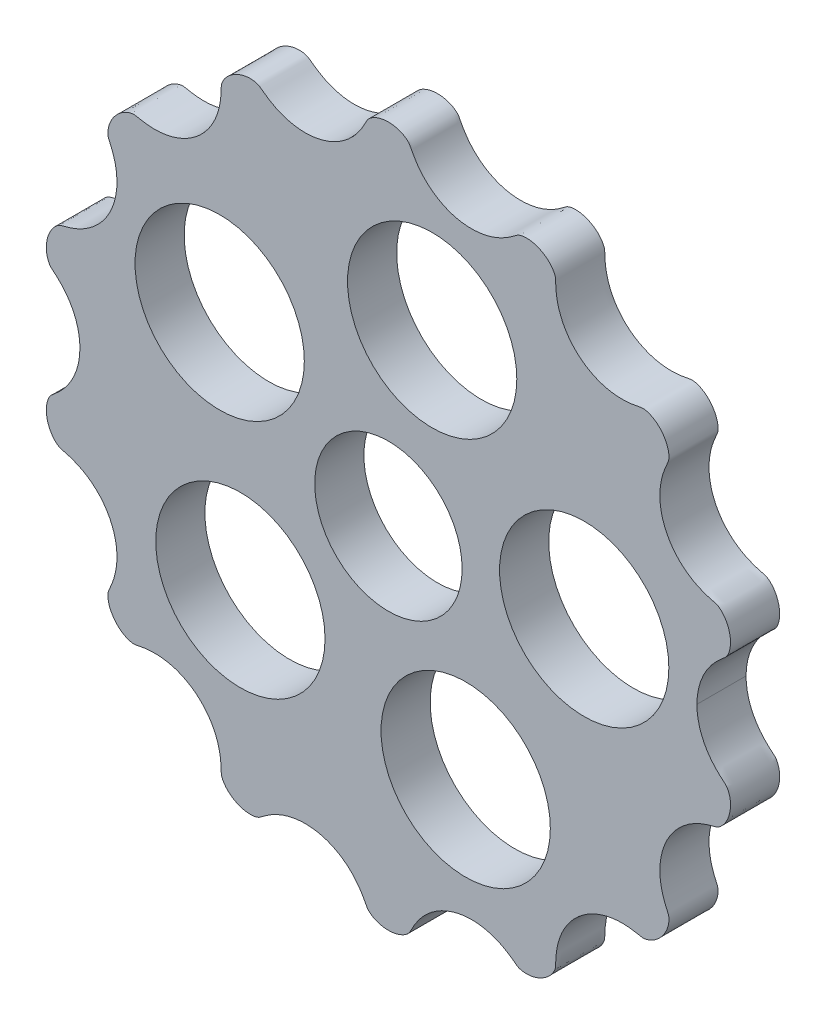
SolidWorks part; units mm, degrees
ref_plane "Front Plane" through (0, 0, 0) normal (0, 0, 1) x (1, 0, 0)
ref_plane "Top Plane" through (0, 0, 0) normal (0, 1, 0) x (1, 0, 0)
ref_plane "Right Plane" through (0, 0, 0) normal (1, 0, 0) x (0, 0, -1)
sketch "Sketch1" plane through (0, 0, 0) normal (0, 0, 1) x (1, 0, 0)
  line L0 (0, 0) -> (-50000, 0) construction
  spline S0 degree 4 poles (29.1148, 12.3034) (29.2251, 12.1678) (29.4552, 11.9043) (29.8276, 11.5337) (30.3727, 11.0937) (30.9601, 10.7121) (31.5053, 10.4321) (31.9903, 10.2313) (32.3732, 10.0998) (32.6459, 10.0172) (32.8897, 9.9508) (33.0761, 9.9023) (33.2365, 9.8624) (33.3649, 9.8232) (33.4599, 9.7833) (33.5683, 9.724) (33.7097, 9.6282) (33.879, 9.4852) (34.0743, 9.2772) (34.2676, 9.0162) (34.4376, 8.7246) (34.5807, 8.4046) (34.6855, 8.0862) (34.7563, 7.7736) (34.7922, 7.5075) (34.8058, 7.2895) (34.8069, 7.1092) (34.8014, 6.9663) (34.7862, 6.7987) (34.7706, 6.683) (34.7382, 6.5037) (34.7005, 6.3555) (34.6486, 6.1898) (34.5809, 6.02) (34.5049, 5.8706) (34.4228, 5.7426) (34.3425, 5.6471) (34.2725, 5.5788) (34.187, 5.5045) (34.0883, 5.422) (33.948, 5.3031) (33.7671, 5.1466) (33.5612, 4.9581) (33.2773, 4.6773) (32.9556, 4.3212) (32.6118, 3.8785) (32.2672, 3.3382) (31.9738, 2.7657) (31.7354, 2.1658) (31.5555, 1.5443) (31.4363, 0.9069) (31.3783, 0.2473) (31.3865, -0.4288) (31.4658, -1.1154) (31.6203, -1.8043) (31.8458, -2.4711) (32.1388, -3.1089) (32.4941, -3.7101) (32.8549, -4.1999) (33.1964, -4.5921) (33.4814, -4.8811) (33.6953, -5.0819) (33.8732, -5.2388) (34.0108, -5.3564) (34.1261, -5.4536) (34.2184, -5.5313) (34.3214, -5.6222) (34.4225, -5.7386) (34.5266, -5.9067) (34.6282, -6.1245) (34.7436, -6.4751) (34.8225, -6.9675) (34.8113, -7.5644) (34.661, -8.2417) (34.4218, -8.7837) (34.1503, -9.1912) (33.9029, -9.4619) (33.7187, -9.6221) (33.5394, -9.7456) (33.3669, -9.8285) (33.1823, -9.875) (33.0004, -9.9222) (32.782, -9.9793) (32.5292, -10.0512) (32.2433, -10.1425) (31.9268, -10.2589) (31.5377, -10.4223) (31.0835, -10.6476) (30.5742, -10.9541) (30.0282, -11.3617) (29.5242, -11.8241) (29.0684, -12.3375) (28.6707, -12.8905) (28.3339, -13.4763) (28.0598, -14.0888) (27.8495, -14.721) (27.7034, -15.3703) (27.6226, -16.0301) (27.6072, -16.6913) (27.6498, -17.2659) (27.7252, -17.7525) (27.8131, -18.1525) (27.8983, -18.4699) (27.9979, -18.7839) (28.1112, -19.094) (28.2196, -19.3578) (28.3162, -19.5777) (28.3886, -19.7384) (28.4347, -19.8413) (28.4769, -19.9459) (28.514, -20.0632) (28.5372, -20.2141) (28.546, -20.4211) (28.5287, -20.6643) (28.4793, -20.9385) (28.3904, -21.239) (28.2361, -21.6133) (27.9894, -22.0397) (27.6291, -22.4842) (27.199, -22.8485) (26.7944, -23.0902) (26.4653, -23.2258) (26.2334, -23.2927) (26.0388, -23.3257) (25.8855, -23.3344) (25.7494, -23.3208) (25.6312, -23.2987) (25.5035, -23.273) (25.3658, -23.2457) (25.1784, -23.2099) (24.8616, -23.1554) (24.425, -23.0993) (23.8669, -23.0674) (23.2277, -23.0884) (22.5933, -23.1683) (21.9654, -23.3085) (21.3502, -23.5092) (20.7566, -23.7687) (20.1904, -24.0849) (19.6475, -24.4614) (19.1353, -24.898) (18.6611, -25.3942) (18.2334, -25.9477) (17.8666, -26.541) (17.564, -27.1671) (17.3278, -27.818) (17.1796, -28.4029) (17.0935, -28.9116) (17.0509, -29.3082) (17.0309, -29.5904) (17.0202, -29.8431) (17.0147, -30.024) (17.0118, -30.1633) (17.0063, -30.2747) (16.9973, -30.3772) (16.9693, -30.5107) (16.9011, -30.6949) (16.7913, -30.9103) (16.5868, -31.2168) (16.2505, -31.5811) (15.7762, -31.9413) (15.1518, -32.2436) (14.5767, -32.3922) (14.0855, -32.431) (13.7189, -32.4031) (13.4803, -32.3569) (13.2942, -32.2977) (13.1612, -32.2347) (13.057, -32.1661) (12.9743, -32.1051) (12.872, -32.0278) (12.749, -31.9353) (12.5773, -31.8086) (12.354, -31.6518) (12.0257, -31.4379) (11.5814, -31.1844) (11.0404, -30.9303) (10.3942, -30.7013) (9.7255, -30.5379) (8.8696, -30.4195) (7.848, -30.4197) (6.8473, -30.5909) (5.9007, -30.9223) (5.1715, -31.2902) (4.6199, -31.6398) (4.1067, -32.0394) (3.6361, -32.4843) (3.2632, -32.9099) (2.973, -33.297) (2.7505, -33.6331) (2.6046, -33.8748) (2.4861, -34.0858) (2.3942, -34.2578) (2.3258, -34.3891) (2.2611, -34.5147) (2.1993, -34.6346) (2.1237, -34.762) (2.0189, -34.8849) (1.8703, -35.0205) (1.6749, -35.1617) (1.435, -35.2974) (1.1501, -35.4193) (0.7695, -35.5374) (0.2868, -35.6195) (-0.2046, -35.6253) (-0.6907, -35.5547) (-1.0776, -35.4449) (-1.3681, -35.3293) (-1.6139, -35.199) (-1.8161, -35.0628) (-1.9708, -34.931) (-2.084, -34.8131) (-2.1593, -34.7039) (-2.2091, -34.6147) (-2.2564, -34.5243) (-2.306, -34.4275) (-2.3668, -34.31) (-2.4588, -34.136) (-2.577, -33.9223) (-2.7226, -33.6774) (-2.945, -33.3365) (-3.2355, -32.9437) (-3.6093, -32.5119) (-4.0817, -32.0607) (-4.5974, -31.6554) (-5.1525, -31.3008) (-5.8873, -30.9274) (-6.8394, -30.5923) (-7.8448, -30.4197) (-8.8696, -30.4195) (-9.7255, -30.5379) (-10.3942, -30.7013) (-11.0404, -30.9303) (-11.5814, -31.1844) (-12.0257, -31.4379) (-12.354, -31.6518) (-12.5773, -31.8086) (-12.749, -31.9353) (-12.872, -32.0278) (-12.9743, -32.1051) (-13.057, -32.1661) (-13.1612, -32.2347) (-13.2942, -32.2977) (-13.4803, -32.3569) (-13.7189, -32.4031) (-14.0855, -32.431) (-14.5767, -32.3922) (-15.1518, -32.2436) (-15.7762, -31.9413) (-16.2505, -31.5811) (-16.5868, -31.2168) (-16.7913, -30.9103) (-16.9011, -30.6949) (-16.9693, -30.5107) (-16.9973, -30.3772) (-17.0063, -30.2747) (-17.0118, -30.1633) (-17.0147, -30.024) (-17.0202, -29.8431) (-17.0309, -29.5904) (-17.0509, -29.3082) (-17.0935, -28.9116) (-17.1796, -28.4029) (-17.3278, -27.818) (-17.564, -27.1671) (-17.8666, -26.541) (-18.2334, -25.9477) (-18.6611, -25.3942) (-19.1353, -24.898) (-19.6475, -24.4614) (-20.1904, -24.0849) (-20.7566, -23.7687) (-21.3502, -23.5092) (-21.9654, -23.3085) (-22.5933, -23.1683) (-23.2277, -23.0884) (-23.8669, -23.0674) (-24.425, -23.0993) (-24.8616, -23.1554) (-25.1784, -23.2099) (-25.3658, -23.2457) (-25.5035, -23.273) (-25.6312, -23.2987) (-25.7494, -23.3208) (-25.8855, -23.3344) (-26.0388, -23.3257) (-26.2334, -23.2927) (-26.4653, -23.2258) (-26.7944, -23.0902) (-27.199, -22.8485) (-27.6291, -22.4842) (-27.9894, -22.0397) (-28.2361, -21.6133) (-28.3904, -21.239) (-28.4793, -20.9385) (-28.5287, -20.6643) (-28.546, -20.4211) (-28.5372, -20.2141) (-28.514, -20.0632) (-28.4769, -19.9459) (-28.4347, -19.8413) (-28.3886, -19.7384) (-28.3162, -19.5777) (-28.2196, -19.3578) (-28.1112, -19.094) (-27.9979, -18.7839) (-27.8983, -18.4699) (-27.8131, -18.1525) (-27.7252, -17.7525) (-27.6498, -17.2659) (-27.6072, -16.6913) (-27.6226, -16.0301) (-27.7034, -15.3703) (-27.8495, -14.721) (-28.0598, -14.0888) (-28.3339, -13.4763) (-28.6707, -12.8905) (-29.0684, -12.3375) (-29.5242, -11.8241) (-30.0282, -11.3617) (-30.5742, -10.9541) (-31.0835, -10.6476) (-31.5377, -10.4223) (-31.9268, -10.2589) (-32.2433, -10.1425) (-32.5292, -10.0512) (-32.782, -9.9793) (-33.0004, -9.9222) (-33.1823, -9.875) (-33.3669, -9.8285) (-33.5394, -9.7456) (-33.7187, -9.6221) (-33.9029, -9.4619) (-34.1503, -9.1912) (-34.4218, -8.7837) (-34.661, -8.2417) (-34.8113, -7.5644) (-34.8225, -6.9675) (-34.7436, -6.4751) (-34.6282, -6.1245) (-34.5266, -5.9067) (-34.4225, -5.7386) (-34.3214, -5.6222) (-34.2184, -5.5313) (-34.1261, -5.4536) (-34.0108, -5.3564) (-33.8732, -5.2388) (-33.6953, -5.0819) (-33.4814, -4.8811) (-33.1964, -4.5921) (-32.8549, -4.1999) (-32.4941, -3.7101) (-32.1388, -3.1089) (-31.8458, -2.4711) (-31.6203, -1.8043) (-31.4658, -1.1154) (-31.3865, -0.4288) (-31.3783, 0.2473) (-31.4363, 0.9069) (-31.5555, 1.5443) (-31.7354, 2.1658) (-31.9738, 2.7657) (-32.2672, 3.3382) (-32.6118, 3.8785) (-32.9556, 4.3212) (-33.2773, 4.6773) (-33.5612, 4.9581) (-33.7671, 5.1466) (-33.948, 5.3031) (-34.0883, 5.422) (-34.187, 5.5045) (-34.2725, 5.5788) (-34.3425, 5.6471) (-34.4228, 5.7426) (-34.5049, 5.8706) (-34.5809, 6.02) (-34.6486, 6.1898) (-34.7005, 6.3555) (-34.7382, 6.5037) (-34.7706, 6.683) (-34.7862, 6.7987) (-34.8014, 6.9663) (-34.8069, 7.1092) (-34.8058, 7.2895) (-34.7922, 7.5075) (-34.7563, 7.7736) (-34.6855, 8.0862) (-34.5807, 8.4046) (-34.4376, 8.7246) (-34.2676, 9.0162) (-34.0743, 9.2772) (-33.879, 9.4852) (-33.7097, 9.6282) (-33.5683, 9.724) (-33.4599, 9.7833) (-33.3649, 9.8232) (-33.2365, 9.8624) (-33.0761, 9.9023) (-32.8897, 9.9508) (-32.6459, 10.0172) (-32.3732, 10.0998) (-31.9903, 10.2313) (-31.5053, 10.4321) (-30.9601, 10.7121) (-30.3727, 11.0937) (-29.8276, 11.5337) (-29.4552, 11.9043) (-29.2251, 12.1678) (-29.1148, 12.3034) knots 0 0 0 0 0 0.004405 0.008809 0.013214 0.01762 0.022025 0.024227 0.02643 0.027817 0.029205 0.030592 0.031286 0.031979 0.032583 0.033187 0.034394 0.036274 0.038154 0.040358 0.042562 0.044765 0.046967 0.048794 0.050621 0.051534 0.052447 0.053361 0.054274 0.055285 0.056296 0.057308 0.058319 0.059613 0.060907 0.061522 0.062138 0.062754 0.06337 0.064374 0.065379 0.067388 0.069397 0.071406 0.075439 0.079471 0.083501 0.087531 0.091623 0.095714 0.099779 0.103843 0.108282 0.112722 0.117161 0.121601 0.125988 0.130375 0.134727 0.136903 0.13908 0.1406 0.14212 0.14288 0.14364 0.1444 0.14516 0.146336 0.147512 0.14936 0.151209 0.15561 0.160014 0.164295 0.16858 0.170438 0.172297 0.173509 0.174721 0.175908 0.177095 0.178282 0.179469 0.181593 0.183717 0.185841 0.187965 0.192223 0.19648 0.200793 0.205106 0.209428 0.213749 0.217927 0.222104 0.226307 0.23051 0.234668 0.238827 0.242946 0.245005 0.247065 0.249144 0.251223 0.253303 0.255382 0.256328 0.257274 0.257748 0.258221 0.259167 0.260371 0.261575 0.263436 0.265296 0.267377 0.269458 0.273617 0.277665 0.281712 0.283577 0.285441 0.286612 0.287783 0.288539 0.289296 0.290053 0.290809 0.291822 0.292834 0.294859 0.29891 0.302906 0.306903 0.310951 0.314999 0.319092 0.323184 0.327249 0.331314 0.335714 0.340113 0.344511 0.348908 0.353257 0.357607 0.361927 0.364088 0.366248 0.367652 0.369056 0.37046 0.370811 0.371162 0.371864 0.373051 0.374238 0.376092 0.377946 0.382309 0.386671 0.390993 0.395318 0.397173 0.399028 0.40023 0.401432 0.402078 0.402725 0.403371 0.404018 0.40531 0.406603 0.408748 0.410892 0.415181 0.419482 0.423784 0.42814 0.432496 0.441216 0.449419 0.453546 0.457674 0.461762 0.465851 0.469909 0.473968 0.476 0.478032 0.480064 0.48108 0.482096 0.482945 0.483794 0.484643 0.485492 0.486669 0.487847 0.489701 0.491555 0.493598 0.495641 0.499725 0.503848 0.50591 0.507972 0.509842 0.511712 0.512906 0.514101 0.514957 0.515814 0.516243 0.516671 0.517528 0.518553 0.519579 0.521629 0.52368 0.525731 0.529831 0.533932 0.538049 0.542166 0.546333 0.550501 0.558784 0.567504 0.57186 0.576216 0.580518 0.584819 0.589108 0.591252 0.593397 0.59469 0.595982 0.596629 0.597275 0.597922 0.598568 0.59977 0.600972 0.602827 0.604682 0.609007 0.613329 0.617691 0.622054 0.623908 0.625762 0.626949 0.628136 0.628838 0.629189 0.62954 0.630944 0.632348 0.633752 0.635912 0.638073 0.642393 0.646743 0.651092 0.655489 0.659887 0.664286 0.668686 0.672751 0.676816 0.680908 0.685001 0.689049 0.693097 0.697094 0.70109 0.705141 0.707166 0.708178 0.709191 0.709947 0.710704 0.711461 0.712217 0.713388 0.714559 0.716423 0.718288 0.722335 0.726383 0.730542 0.732623 0.734704 0.736564 0.738425 0.739629 0.740833 0.741779 0.742252 0.742726 0.743672 0.744618 0.746697 0.748777 0.750856 0.752935 0.754995 0.757054 0.761173 0.765332 0.76949 0.773693 0.777896 0.782073 0.786251 0.790572 0.794894 0.799207 0.80352 0.807777 0.812035 0.814159 0.816283 0.818407 0.820531 0.821718 0.822905 0.824092 0.825279 0.826491 0.827703 0.829562 0.83142 0.835705 0.839986 0.84439 0.848791 0.85064 0.852488 0.853664 0.85484 0.8556 0.85636 0.85712 0.85788 0.8594 0.86092 0.863097 0.865273 0.869625 0.874012 0.878399 0.882839 0.887278 0.891718 0.896157 0.900221 0.904286 0.908377 0.912469 0.916499 0.920529 0.924561 0.928594 0.930603 0.932612 0.934621 0.935626 0.93663 0.937246 0.937862 0.938478 0.939093 0.940387 0.941681 0.942692 0.943704 0.944715 0.945726 0.946639 0.947553 0.948466 0.949379 0.951206 0.953033 0.955235 0.957438 0.959642 0.961846 0.963726 0.965606 0.966813 0.967417 0.968021 0.968714 0.969408 0.970795 0.972183 0.97357 0.975773 0.977975 0.98238 0.986786 0.991191 0.995595 1 1 1 1 1 construction
  spline S1 degree 4 poles (31.3875, 0) (31.3875, -0.1914) (31.4016, -0.559) (31.4625, -1.1005) (31.6203, -1.8043) (31.8458, -2.4711) (32.1388, -3.1089) (32.4941, -3.7101) (32.8549, -4.1999) (33.1964, -4.5921) (33.4814, -4.8811) (33.6953, -5.0819) (33.8732, -5.2388) (34.0108, -5.3564) (34.1261, -5.4536) (34.2184, -5.5313) (34.3214, -5.6222) (34.4225, -5.7386) (34.5266, -5.9067) (34.6282, -6.1245) (34.7436, -6.4751) (34.8225, -6.9675) (34.8113, -7.5644) (34.661, -8.2417) (34.4218, -8.7837) (34.1503, -9.1912) (33.9029, -9.4619) (33.7187, -9.6221) (33.5394, -9.7456) (33.3669, -9.8285) (33.1823, -9.875) (33.0004, -9.9222) (32.782, -9.9793) (32.5292, -10.0512) (32.2433, -10.1425) (31.9268, -10.2589) (31.5377, -10.4223) (31.0835, -10.6476) (30.5742, -10.9541) (30.0282, -11.3617) (29.5242, -11.8241) (29.0684, -12.3375) (28.6707, -12.8905) (28.3339, -13.4763) (28.0598, -14.0888) (27.8495, -14.721) (27.7034, -15.3703) (27.6226, -16.0301) (27.6072, -16.6913) (27.6498, -17.2659) (27.7252, -17.7525) (27.8131, -18.1525) (27.8983, -18.4699) (27.9979, -18.7839) (28.1112, -19.094) (28.2196, -19.3578) (28.3162, -19.5777) (28.3886, -19.7384) (28.4347, -19.8413) (28.4769, -19.9459) (28.514, -20.0632) (28.5372, -20.2141) (28.546, -20.4211) (28.5287, -20.6643) (28.4793, -20.9385) (28.3904, -21.239) (28.2361, -21.6133) (27.9894, -22.0397) (27.6291, -22.4842) (27.199, -22.8485) (26.7944, -23.0902) (26.4653, -23.2258) (26.2334, -23.2927) (26.0388, -23.3257) (25.8855, -23.3344) (25.7494, -23.3208) (25.6312, -23.2987) (25.5035, -23.273) (25.3658, -23.2457) (25.1784, -23.2099) (24.8616, -23.1554) (24.425, -23.0993) (23.8669, -23.0674) (23.2277, -23.0884) (22.5933, -23.1683) (21.9654, -23.3085) (21.3502, -23.5092) (20.7566, -23.7687) (20.1904, -24.0849) (19.6475, -24.4614) (19.1353, -24.898) (18.6611, -25.3942) (18.2334, -25.9477) (17.8666, -26.541) (17.564, -27.1671) (17.3278, -27.818) (17.1796, -28.4029) (17.0935, -28.9116) (17.0509, -29.3082) (17.0309, -29.5904) (17.0202, -29.8431) (17.0147, -30.024) (17.0118, -30.1633) (17.0063, -30.2747) (16.9973, -30.3772) (16.9693, -30.5107) (16.9011, -30.6949) (16.7913, -30.9103) (16.5868, -31.2168) (16.2505, -31.5811) (15.7762, -31.9413) (15.1518, -32.2436) (14.5767, -32.3922) (14.0855, -32.431) (13.7189, -32.4031) (13.4803, -32.3569) (13.2942, -32.2977) (13.1612, -32.2347) (13.057, -32.1661) (12.9743, -32.1051) (12.872, -32.0278) (12.749, -31.9353) (12.5773, -31.8086) (12.354, -31.6518) (12.0257, -31.4379) (11.5814, -31.1844) (11.0404, -30.9303) (10.3942, -30.7013) (9.7255, -30.5379) (8.8696, -30.4195) (7.848, -30.4197) (6.8473, -30.5909) (5.9007, -30.9223) (5.1715, -31.2902) (4.6199, -31.6398) (4.1067, -32.0394) (3.6361, -32.4843) (3.2632, -32.9099) (2.973, -33.297) (2.7505, -33.6331) (2.6046, -33.8748) (2.4861, -34.0858) (2.3942, -34.2578) (2.3258, -34.3891) (2.2611, -34.5147) (2.1993, -34.6346) (2.1237, -34.762) (2.0189, -34.8849) (1.8703, -35.0205) (1.6749, -35.1617) (1.435, -35.2974) (1.1501, -35.4193) (0.7695, -35.5374) (0.2868, -35.6195) (-0.2046, -35.6253) (-0.6907, -35.5547) (-1.0776, -35.4449) (-1.3681, -35.3293) (-1.6139, -35.199) (-1.8161, -35.0628) (-1.9708, -34.931) (-2.084, -34.8131) (-2.1593, -34.7039) (-2.2091, -34.6147) (-2.2564, -34.5243) (-2.306, -34.4275) (-2.3668, -34.31) (-2.4588, -34.136) (-2.577, -33.9223) (-2.7226, -33.6774) (-2.945, -33.3365) (-3.2355, -32.9437) (-3.6093, -32.5119) (-4.0817, -32.0607) (-4.5974, -31.6554) (-5.1525, -31.3008) (-5.8873, -30.9274) (-6.8394, -30.5923) (-7.8448, -30.4197) (-8.8696, -30.4195) (-9.7255, -30.5379) (-10.3942, -30.7013) (-11.0404, -30.9303) (-11.5814, -31.1844) (-12.0257, -31.4379) (-12.354, -31.6518) (-12.5773, -31.8086) (-12.749, -31.9353) (-12.872, -32.0278) (-12.9743, -32.1051) (-13.057, -32.1661) (-13.1612, -32.2347) (-13.2942, -32.2977) (-13.4803, -32.3569) (-13.7189, -32.4031) (-14.0855, -32.431) (-14.5767, -32.3922) (-15.1518, -32.2436) (-15.7762, -31.9413) (-16.2505, -31.5811) (-16.5868, -31.2168) (-16.7913, -30.9103) (-16.9011, -30.6949) (-16.9693, -30.5107) (-16.9973, -30.3772) (-17.0063, -30.2747) (-17.0118, -30.1633) (-17.0147, -30.024) (-17.0202, -29.8431) (-17.0309, -29.5904) (-17.0509, -29.3082) (-17.0935, -28.9116) (-17.1796, -28.4029) (-17.3278, -27.818) (-17.564, -27.1671) (-17.8666, -26.541) (-18.2334, -25.9477) (-18.6611, -25.3942) (-19.1353, -24.898) (-19.6475, -24.4614) (-20.1904, -24.0849) (-20.7566, -23.7687) (-21.3502, -23.5092) (-21.9654, -23.3085) (-22.5933, -23.1683) (-23.2277, -23.0884) (-23.8669, -23.0674) (-24.425, -23.0993) (-24.8616, -23.1554) (-25.1784, -23.2099) (-25.3658, -23.2457) (-25.5035, -23.273) (-25.6312, -23.2987) (-25.7494, -23.3208) (-25.8855, -23.3344) (-26.0388, -23.3257) (-26.2334, -23.2927) (-26.4653, -23.2258) (-26.7944, -23.0902) (-27.199, -22.8485) (-27.6291, -22.4842) (-27.9894, -22.0397) (-28.2361, -21.6133) (-28.3904, -21.239) (-28.4793, -20.9385) (-28.5287, -20.6643) (-28.546, -20.4211) (-28.5372, -20.2141) (-28.514, -20.0632) (-28.4769, -19.9459) (-28.4347, -19.8413) (-28.3886, -19.7384) (-28.3162, -19.5777) (-28.2196, -19.3578) (-28.1112, -19.094) (-27.9979, -18.7839) (-27.8983, -18.4699) (-27.8131, -18.1525) (-27.7252, -17.7525) (-27.6498, -17.2659) (-27.6072, -16.6913) (-27.6226, -16.0301) (-27.7034, -15.3703) (-27.8495, -14.721) (-28.0598, -14.0888) (-28.3339, -13.4763) (-28.6707, -12.8905) (-29.0684, -12.3375) (-29.5242, -11.8241) (-30.0282, -11.3617) (-30.5742, -10.9541) (-31.0835, -10.6476) (-31.5377, -10.4223) (-31.9268, -10.2589) (-32.2433, -10.1425) (-32.5292, -10.0512) (-32.782, -9.9793) (-33.0004, -9.9222) (-33.1823, -9.875) (-33.3669, -9.8285) (-33.5394, -9.7456) (-33.7187, -9.6221) (-33.9029, -9.4619) (-34.1503, -9.1912) (-34.4218, -8.7837) (-34.661, -8.2417) (-34.8113, -7.5644) (-34.8225, -6.9675) (-34.7436, -6.4751) (-34.6282, -6.1245) (-34.5266, -5.9067) (-34.4225, -5.7386) (-34.3214, -5.6222) (-34.2184, -5.5313) (-34.1261, -5.4536) (-34.0108, -5.3564) (-33.8732, -5.2388) (-33.6953, -5.0819) (-33.4814, -4.8811) (-33.1964, -4.5921) (-32.8549, -4.1999) (-32.4941, -3.7101) (-32.1388, -3.1089) (-31.8458, -2.4711) (-31.5589, -1.6226) (-31.4275, -0.9114) (-31.3875, -0.3676) (-31.3875, 0) knots 0.103459 0.103459 0.103459 0.103459 0.103459 0.108282 0.112722 0.117161 0.121601 0.125988 0.130375 0.134727 0.136903 0.13908 0.1406 0.14212 0.14288 0.14364 0.1444 0.14516 0.146336 0.147512 0.14936 0.151209 0.15561 0.160014 0.164295 0.16858 0.170438 0.172297 0.173509 0.174721 0.175908 0.177095 0.178282 0.179469 0.181593 0.183717 0.185841 0.187965 0.192223 0.19648 0.200793 0.205106 0.209428 0.213749 0.217927 0.222104 0.226307 0.23051 0.234668 0.238827 0.242946 0.245005 0.247065 0.249144 0.251223 0.253303 0.255382 0.256328 0.257274 0.257748 0.258221 0.259167 0.260371 0.261575 0.263436 0.265296 0.267377 0.269458 0.273617 0.277665 0.281712 0.283577 0.285441 0.286612 0.287783 0.288539 0.289296 0.290053 0.290809 0.291822 0.292834 0.294859 0.29891 0.302906 0.306903 0.310951 0.314999 0.319092 0.323184 0.327249 0.331314 0.335714 0.340113 0.344511 0.348908 0.353257 0.357607 0.361927 0.364088 0.366248 0.367652 0.369056 0.37046 0.370811 0.371162 0.371864 0.373051 0.374238 0.376092 0.377946 0.382309 0.386671 0.390993 0.395318 0.397173 0.399028 0.40023 0.401432 0.402078 0.402725 0.403371 0.404018 0.40531 0.406603 0.408748 0.410892 0.415181 0.419482 0.423784 0.42814 0.432496 0.441216 0.449419 0.453546 0.457674 0.461762 0.465851 0.469909 0.473968 0.476 0.478032 0.480064 0.48108 0.482096 0.482945 0.483794 0.484643 0.485492 0.486669 0.487847 0.489701 0.491555 0.493598 0.495641 0.499725 0.503848 0.50591 0.507972 0.509842 0.511712 0.512906 0.514101 0.514957 0.515814 0.516243 0.516671 0.517528 0.518553 0.519579 0.521629 0.52368 0.525731 0.529831 0.533932 0.538049 0.542166 0.546333 0.550501 0.558784 0.567504 0.57186 0.576216 0.580518 0.584819 0.589108 0.591252 0.593397 0.59469 0.595982 0.596629 0.597275 0.597922 0.598568 0.59977 0.600972 0.602827 0.604682 0.609007 0.613329 0.617691 0.622054 0.623908 0.625762 0.626949 0.628136 0.628838 0.629189 0.62954 0.630944 0.632348 0.633752 0.635912 0.638073 0.642393 0.646743 0.651092 0.655489 0.659887 0.664286 0.668686 0.672751 0.676816 0.680908 0.685001 0.689049 0.693097 0.697094 0.70109 0.705141 0.707166 0.708178 0.709191 0.709947 0.710704 0.711461 0.712217 0.713388 0.714559 0.716423 0.718288 0.722335 0.726383 0.730542 0.732623 0.734704 0.736564 0.738425 0.739629 0.740833 0.741779 0.742252 0.742726 0.743672 0.744618 0.746697 0.748777 0.750856 0.752935 0.754995 0.757054 0.761173 0.765332 0.76949 0.773693 0.777896 0.782073 0.786251 0.790572 0.794894 0.799207 0.80352 0.807777 0.812035 0.814159 0.816283 0.818407 0.820531 0.821718 0.822905 0.824092 0.825279 0.826491 0.827703 0.829562 0.83142 0.835705 0.839986 0.84439 0.848791 0.85064 0.852488 0.853664 0.85484 0.8556 0.85636 0.85712 0.85788 0.8594 0.86092 0.863097 0.865273 0.869625 0.874012 0.878399 0.882839 0.887278 0.896541 0.896541 0.896541 0.896541 0.896541
  spline S2 degree 4 poles (31.3875, 0) (31.3875, 0.1914) (31.4016, 0.559) (31.4625, 1.1005) (31.6203, 1.8043) (31.8458, 2.4711) (32.1388, 3.1089) (32.4941, 3.7101) (32.8549, 4.1999) (33.1964, 4.5921) (33.4814, 4.8811) (33.6953, 5.0819) (33.8732, 5.2388) (34.0108, 5.3564) (34.1261, 5.4536) (34.2184, 5.5313) (34.3214, 5.6222) (34.4225, 5.7386) (34.5266, 5.9067) (34.6282, 6.1245) (34.7436, 6.4751) (34.8225, 6.9675) (34.8113, 7.5644) (34.661, 8.2417) (34.4218, 8.7837) (34.1503, 9.1912) (33.9029, 9.4619) (33.7187, 9.6221) (33.5394, 9.7456) (33.3669, 9.8285) (33.1823, 9.875) (33.0004, 9.9222) (32.782, 9.9793) (32.5292, 10.0512) (32.2433, 10.1425) (31.9268, 10.2589) (31.5377, 10.4223) (31.0835, 10.6476) (30.5742, 10.9541) (30.0282, 11.3617) (29.5242, 11.8241) (29.0684, 12.3375) (28.6707, 12.8905) (28.3339, 13.4763) (28.0598, 14.0888) (27.8495, 14.721) (27.7034, 15.3703) (27.6226, 16.0301) (27.6072, 16.6913) (27.6498, 17.2659) (27.7252, 17.7525) (27.8131, 18.1525) (27.8983, 18.4699) (27.9979, 18.7839) (28.1112, 19.094) (28.2196, 19.3578) (28.3162, 19.5777) (28.3886, 19.7384) (28.4347, 19.8413) (28.4769, 19.9459) (28.514, 20.0632) (28.5372, 20.2141) (28.546, 20.4211) (28.5287, 20.6643) (28.4793, 20.9385) (28.3904, 21.239) (28.2361, 21.6133) (27.9894, 22.0397) (27.6291, 22.4842) (27.199, 22.8485) (26.7944, 23.0902) (26.4653, 23.2258) (26.2334, 23.2927) (26.0388, 23.3257) (25.8855, 23.3344) (25.7494, 23.3208) (25.6312, 23.2987) (25.5035, 23.273) (25.3658, 23.2457) (25.1784, 23.2099) (24.8616, 23.1554) (24.425, 23.0993) (23.8669, 23.0674) (23.2277, 23.0884) (22.5933, 23.1683) (21.9654, 23.3085) (21.3502, 23.5092) (20.7566, 23.7687) (20.1904, 24.0849) (19.6475, 24.4614) (19.1353, 24.898) (18.6611, 25.3942) (18.2334, 25.9477) (17.8666, 26.541) (17.564, 27.1671) (17.3278, 27.818) (17.1796, 28.4029) (17.0935, 28.9116) (17.0509, 29.3082) (17.0309, 29.5904) (17.0202, 29.8431) (17.0147, 30.024) (17.0118, 30.1633) (17.0063, 30.2747) (16.9973, 30.3772) (16.9693, 30.5107) (16.9011, 30.6949) (16.7913, 30.9103) (16.5868, 31.2168) (16.2505, 31.5811) (15.7762, 31.9413) (15.1518, 32.2436) (14.5767, 32.3922) (14.0855, 32.431) (13.7189, 32.4031) (13.4803, 32.3569) (13.2942, 32.2977) (13.1612, 32.2347) (13.057, 32.1661) (12.9743, 32.1051) (12.872, 32.0278) (12.749, 31.9353) (12.5773, 31.8086) (12.354, 31.6518) (12.0257, 31.4379) (11.5814, 31.1844) (11.0404, 30.9303) (10.3942, 30.7013) (9.7255, 30.5379) (8.8696, 30.4195) (7.848, 30.4197) (6.8473, 30.5909) (5.9007, 30.9223) (5.1715, 31.2902) (4.6199, 31.6398) (4.1067, 32.0394) (3.6361, 32.4843) (3.2632, 32.9099) (2.973, 33.297) (2.7505, 33.6331) (2.6046, 33.8748) (2.4861, 34.0858) (2.3942, 34.2578) (2.3258, 34.3891) (2.2611, 34.5147) (2.1993, 34.6346) (2.1237, 34.762) (2.0189, 34.8849) (1.8703, 35.0205) (1.6749, 35.1617) (1.435, 35.2974) (1.1501, 35.4193) (0.7695, 35.5374) (0.2868, 35.6195) (-0.2046, 35.6253) (-0.6907, 35.5547) (-1.0776, 35.4449) (-1.3681, 35.3293) (-1.6139, 35.199) (-1.8161, 35.0628) (-1.9708, 34.931) (-2.084, 34.8131) (-2.1593, 34.7039) (-2.2091, 34.6147) (-2.2564, 34.5243) (-2.306, 34.4275) (-2.3668, 34.31) (-2.4588, 34.136) (-2.577, 33.9223) (-2.7226, 33.6774) (-2.945, 33.3365) (-3.2355, 32.9437) (-3.6093, 32.5119) (-4.0817, 32.0607) (-4.5974, 31.6554) (-5.1525, 31.3008) (-5.8873, 30.9274) (-6.8394, 30.5923) (-7.8448, 30.4197) (-8.8696, 30.4195) (-9.7255, 30.5379) (-10.3942, 30.7013) (-11.0404, 30.9303) (-11.5814, 31.1844) (-12.0257, 31.4379) (-12.354, 31.6518) (-12.5773, 31.8086) (-12.749, 31.9353) (-12.872, 32.0278) (-12.9743, 32.1051) (-13.057, 32.1661) (-13.1612, 32.2347) (-13.2942, 32.2977) (-13.4803, 32.3569) (-13.7189, 32.4031) (-14.0855, 32.431) (-14.5767, 32.3922) (-15.1518, 32.2436) (-15.7762, 31.9413) (-16.2505, 31.5811) (-16.5868, 31.2168) (-16.7913, 30.9103) (-16.9011, 30.6949) (-16.9693, 30.5107) (-16.9973, 30.3772) (-17.0063, 30.2747) (-17.0118, 30.1633) (-17.0147, 30.024) (-17.0202, 29.8431) (-17.0309, 29.5904) (-17.0509, 29.3082) (-17.0935, 28.9116) (-17.1796, 28.4029) (-17.3278, 27.818) (-17.564, 27.1671) (-17.8666, 26.541) (-18.2334, 25.9477) (-18.6611, 25.3942) (-19.1353, 24.898) (-19.6475, 24.4614) (-20.1904, 24.0849) (-20.7566, 23.7687) (-21.3502, 23.5092) (-21.9654, 23.3085) (-22.5933, 23.1683) (-23.2277, 23.0884) (-23.8669, 23.0674) (-24.425, 23.0993) (-24.8616, 23.1554) (-25.1784, 23.2099) (-25.3658, 23.2457) (-25.5035, 23.273) (-25.6312, 23.2987) (-25.7494, 23.3208) (-25.8855, 23.3344) (-26.0388, 23.3257) (-26.2334, 23.2927) (-26.4653, 23.2258) (-26.7944, 23.0902) (-27.199, 22.8485) (-27.6291, 22.4842) (-27.9894, 22.0397) (-28.2361, 21.6133) (-28.3904, 21.239) (-28.4793, 20.9385) (-28.5287, 20.6643) (-28.546, 20.4211) (-28.5372, 20.2141) (-28.514, 20.0632) (-28.4769, 19.9459) (-28.4347, 19.8413) (-28.3886, 19.7384) (-28.3162, 19.5777) (-28.2196, 19.3578) (-28.1112, 19.094) (-27.9979, 18.7839) (-27.8983, 18.4699) (-27.8131, 18.1525) (-27.7252, 17.7525) (-27.6498, 17.2659) (-27.6072, 16.6913) (-27.6226, 16.0301) (-27.7034, 15.3703) (-27.8495, 14.721) (-28.0598, 14.0888) (-28.3339, 13.4763) (-28.6707, 12.8905) (-29.0684, 12.3375) (-29.5242, 11.8241) (-30.0282, 11.3617) (-30.5742, 10.9541) (-31.0835, 10.6476) (-31.5377, 10.4223) (-31.9268, 10.2589) (-32.2433, 10.1425) (-32.5292, 10.0512) (-32.782, 9.9793) (-33.0004, 9.9222) (-33.1823, 9.875) (-33.3669, 9.8285) (-33.5394, 9.7456) (-33.7187, 9.6221) (-33.9029, 9.4619) (-34.1503, 9.1912) (-34.4218, 8.7837) (-34.661, 8.2417) (-34.8113, 7.5644) (-34.8225, 6.9675) (-34.7436, 6.4751) (-34.6282, 6.1245) (-34.5266, 5.9067) (-34.4225, 5.7386) (-34.3214, 5.6222) (-34.2184, 5.5313) (-34.1261, 5.4536) (-34.0108, 5.3564) (-33.8732, 5.2388) (-33.6953, 5.0819) (-33.4814, 4.8811) (-33.1964, 4.5921) (-32.8549, 4.1999) (-32.4941, 3.7101) (-32.1388, 3.1089) (-31.8458, 2.4711) (-31.5589, 1.6226) (-31.4275, 0.9114) (-31.3875, 0.3676) (-31.3875, 0) knots 0.103459 0.103459 0.103459 0.103459 0.103459 0.108282 0.112722 0.117161 0.121601 0.125988 0.130375 0.134727 0.136903 0.13908 0.1406 0.14212 0.14288 0.14364 0.1444 0.14516 0.146336 0.147512 0.14936 0.151209 0.15561 0.160014 0.164295 0.16858 0.170438 0.172297 0.173509 0.174721 0.175908 0.177095 0.178282 0.179469 0.181593 0.183717 0.185841 0.187965 0.192223 0.19648 0.200793 0.205106 0.209428 0.213749 0.217927 0.222104 0.226307 0.23051 0.234668 0.238827 0.242946 0.245005 0.247065 0.249144 0.251223 0.253303 0.255382 0.256328 0.257274 0.257748 0.258221 0.259167 0.260371 0.261575 0.263436 0.265296 0.267377 0.269458 0.273617 0.277665 0.281712 0.283577 0.285441 0.286612 0.287783 0.288539 0.289296 0.290053 0.290809 0.291822 0.292834 0.294859 0.29891 0.302906 0.306903 0.310951 0.314999 0.319092 0.323184 0.327249 0.331314 0.335714 0.340113 0.344511 0.348908 0.353257 0.357607 0.361927 0.364088 0.366248 0.367652 0.369056 0.37046 0.370811 0.371162 0.371864 0.373051 0.374238 0.376092 0.377946 0.382309 0.386671 0.390993 0.395318 0.397173 0.399028 0.40023 0.401432 0.402078 0.402725 0.403371 0.404018 0.40531 0.406603 0.408748 0.410892 0.415181 0.419482 0.423784 0.42814 0.432496 0.441216 0.449419 0.453546 0.457674 0.461762 0.465851 0.469909 0.473968 0.476 0.478032 0.480064 0.48108 0.482096 0.482945 0.483794 0.484643 0.485492 0.486669 0.487847 0.489701 0.491555 0.493598 0.495641 0.499725 0.503848 0.50591 0.507972 0.509842 0.511712 0.512906 0.514101 0.514957 0.515814 0.516243 0.516671 0.517528 0.518553 0.519579 0.521629 0.52368 0.525731 0.529831 0.533932 0.538049 0.542166 0.546333 0.550501 0.558784 0.567504 0.57186 0.576216 0.580518 0.584819 0.589108 0.591252 0.593397 0.59469 0.595982 0.596629 0.597275 0.597922 0.598568 0.59977 0.600972 0.602827 0.604682 0.609007 0.613329 0.617691 0.622054 0.623908 0.625762 0.626949 0.628136 0.628838 0.629189 0.62954 0.630944 0.632348 0.633752 0.635912 0.638073 0.642393 0.646743 0.651092 0.655489 0.659887 0.664286 0.668686 0.672751 0.676816 0.680908 0.685001 0.689049 0.693097 0.697094 0.70109 0.705141 0.707166 0.708178 0.709191 0.709947 0.710704 0.711461 0.712217 0.713388 0.714559 0.716423 0.718288 0.722335 0.726383 0.730542 0.732623 0.734704 0.736564 0.738425 0.739629 0.740833 0.741779 0.742252 0.742726 0.743672 0.744618 0.746697 0.748777 0.750856 0.752935 0.754995 0.757054 0.761173 0.765332 0.76949 0.773693 0.777896 0.782073 0.786251 0.790572 0.794894 0.799207 0.80352 0.807777 0.812035 0.814159 0.816283 0.818407 0.820531 0.821718 0.822905 0.824092 0.825279 0.826491 0.827703 0.829562 0.83142 0.835705 0.839986 0.84439 0.848791 0.85064 0.852488 0.853664 0.85484 0.8556 0.85636 0.85712 0.85788 0.8594 0.86092 0.863097 0.865273 0.869625 0.874012 0.878399 0.882839 0.887278 0.896541 0.896541 0.896541 0.896541 0.896541
extrude "Boss-Extrude1" add sketch "Sketch1" along normal blind 5
sketch "Sketch2" plane through (0, 0, 5) normal (0, 0, 1) x (1, 0, 0)
  line L0 (0, 0) -> (0, 51.7601) construction
  line L1 (0, 0) -> (4.4504, 19.4986) construction
  circle A0 centre (0, 0) radius 7.5
  circle A1 centre (4.4504, 19.4986) radius 8.6125
  circle A2 centre (19.9195, 1.7928) radius 8.6125
  circle A3 centre (7.8605, -18.3906) radius 8.6125
  circle A4 centre (-15.0614, -13.1588) radius 8.6125
  circle A5 centre (-17.169, 10.258) radius 8.6125
  point P21 (0, 0)
  dimension "D1" = 15
  dimension "D2" = 17.225
  dimension "D3" = 20
  dimension "D5" = 12.857
  dimension "D4" = 5
extrude "Cut-Extrude1" cut sketch "Sketch2" against normal through all and the other way through all
equation "\"roller_radius\"= 6.5"
equation "\"eccentricity\"= \"roller_radius\" * 0.325"
equation "\"outer_radius\"= 40"
equation "\"eccentric_shaft_radius\"= 16"
equation "\"rotor_width\"= 10"
equation "\"housing_depth\"= 40"
equation "\"bottom_depth\"= 5"
equation "\"roller_bearing_OD\"= \"roller_radius\" * 2"
equation "\"roller_bearing_ID\"= 6"
equation "\"eccentric_bearing_ID\"= 6"
equation "\"eccentric_bearing_OD\"= 15"
equation "\"roller_bearing_height\"= 5"
equation "\"eccentric_bearing_height\"= 5"
equation "\"bottom_bearing_ID\"= 15"
equation "\"bottom_bearing_OD\"= 32"
equation "\"bottom_bearing_height\"= 9"
equation "\"distance_to_output_rotor_holes\"= 20"
equation "\"D1@Boss-Extrude1\"=\"roller_bearing_height\""
equation "\"D1@Sketch2\"=\"eccentric_bearing_OD\""
equation "\"D2@Sketch2\"=\"roller_bearing_OD\"+\"eccentricity\"*2"
equation "\"D3@Sketch2\"=\"distance_to_output_rotor_holes\""
equation "\"output_bearing_ID\" = 25"
equation "\"output_bearing_OD\" = 37"
equation "\"output_bearing_height\" = 7"
equation "\"number_of_rollers\" = 15"
equation "\"housing_height\" = 27"
equation "\"spacer_1\" = 7"
equation "\"spacer_2\" = 2.5"
equation "\"spacer_3\" = 7.5"
equation "\"roller_pin_depth\" = 5"
equation "\"D5@Sketch2\"=180/(\"number_of_rollers\"-1)"
